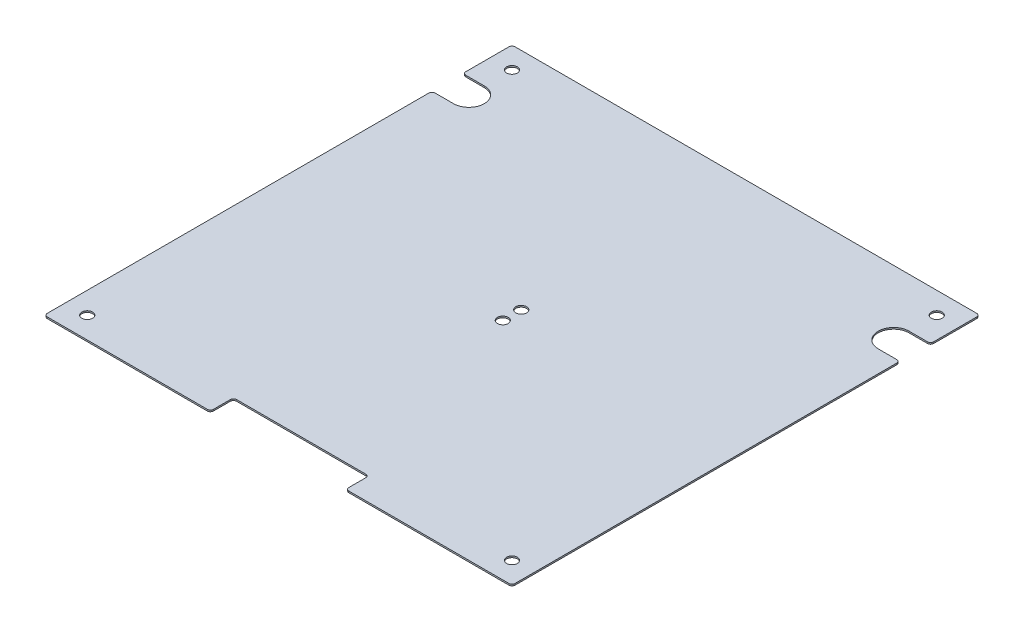
SolidWorks part; units mm, degrees
ref_plane "Front Plane" through (0, 0, 0) normal (0, 0, 1) x (1, 0, 0)
ref_plane "Top Plane" through (0, 0, 0) normal (0, 1, 0) x (1, 0, 0)
ref_plane "Right Plane" through (0, 0, 0) normal (1, 0, 0) x (0, 0, -1)
sketch "Sketch1" plane through (0, 0, 0) normal (0, 1, 0) x (1, 0, 0)
  line L1 (152, -152) -> (-152, -152)
  line L2 (152, -152) -> (152, 152)
  line L3 (152, 152) -> (-152, 152)
  line L4 (-152, -152) -> (-152, 152)
  line L5 (152, -152) -> (-152, 152) construction
  line L6 (152, 152) -> (-152, -152) construction
  point P0 (0, 0)
  dimension "D1" = 304
extrude "Boss-Extrude1" add sketch "Sketch1" along normal blind 1
sketch "Sketch2" plane through (0, 1, 0) normal (0, 1, 0) x (1, 0, 0)
  line L0 (-44, -152) -> (-44, -137)
  line L1 (-152, -152) -> (152, -152) construction
  line L2 (-44, -137) -> (44, -137)
  line L3 (44, -137) -> (44, -152)
  line L4 (44, -152) -> (-44, -152)
  line L5 (-152, 100) -> (-138, 100)
  line L6 (-152, 152) -> (-152, -152) construction
  line L8 (-138, 120) -> (-152, 120)
  line L9 (-152, 120) -> (-152, 100)
  line L10 (-152, 110) -> (-138, 110) construction
  line L11 (0, -152) -> (0, 152) construction
  line L12 (152, 152) -> (-152, 152) construction
  line L13 (152, 100) -> (138, 100)
  line L14 (152, 120) -> (152, 100)
  line L15 (138, 120) -> (152, 120)
  arc A0 (-138, 100) -> (-138, 120) centre (-138, 110) ccw
  arc A1 (138, 100) -> (138, 120) centre (138, 110) cw
  point P14 (0, 0)
  point P20 (0, 0)
  dimension "D1" = 108
  dimension "D2" = 196
  dimension "D3" = 15
  dimension "D4" = 20
  dimension "D5" = 262
  dimension "D6" = 14
extrude "Cut-Extrude1" cut sketch "Sketch2" against normal through all
fillet "Fillet1" radius 2 12 edges at (-44, 0.5, 152) (-152, 0.5, 152) (-152, 0.5, -100) (-152, 0.5, -120) (152, 0.5, -152) (152, 0.5, -120) (152, 0.5, -100) (152, 0.5, 152) (44, 0.5, 152) (44, 0.5, 137) (-44, 0.5, 137) (-152, 0.5, -152)
hole_wizard "Ø7.0 (7) Diameter Hole1" positions "Sketch3" profile "Sketch4" hole size "Ø7.0" standard "ANSI Metric" end condition up to next
sketch "Sketch3" plane through (0, 1, 0) normal (0, 1, 0) x (1, 0, 0)
  line L1 (-138, -138) -> (138, -138)
  line L2 (-138, -138) -> (-138, 138)
  line L3 (-138, 138) -> (138, 138)
  line L4 (138, -138) -> (138, 138)
  line L5 (-152, 98) -> (-152, -150) construction
  line L6 (-150, -152) -> (-46, -152) construction
  line L7 (0, 6) -> (0, -6) construction
  point P1 (-138, -138)
  point P2 (138, 138)
  point P131 (-138, 138)
  point P132 (138, -138)
  point P138 (0, -6)
  point P140 (0, 6)
  dimension "D1" = 14
  dimension "D2" = 14
  dimension "D3" = 290
  dimension "D4" = 290
  dimension "D5" = 152
  dimension "D6" = 146
  dimension "D7" = 158
sketch "Sketch4" plane through (-138, 1, 138) normal (1, 0, 0) x (0, 0, 1)
  line L0 (0, 0) -> (0, 1)
  line L1 (0, 1) -> (3.5, 1)
  line L2 (3.5, 1) -> (3.5, 0)
  line L5 (3.5, 0) -> (0, 0)
  line L11 (0, -6.35) -> (0, 107.95) construction
  dimension "Thru Hole Dia." = 7
  dimension "Thru Hole Depth" = 1
sketch "Sketch6" plane through (0, 0, 0) normal (0, -1, 0) x (1, 0, 0)
  line L0 (46, 152) -> (150, 152) construction
  line L1 (20, 97) -> (-20, 97)
  line L2 (20, 97) -> (20, 122)
  line L3 (20, 122) -> (-20, 122)
  line L4 (-20, 97) -> (-20, 122)
  line L5 (20, 97) -> (-20, 122) construction
  line L6 (20, 122) -> (-20, 97) construction
  point P0 (0, 109.5)
  point P5 (0, 0)
  point P9 (20.6341, 122)
  point P10 (21.0387, 97.9109)
  dimension "D1" = 30
  dimension "D2" = 40
  dimension "D3" = 25
extrude "Boss-Extrude2" add sketch "Sketch6" along normal blind 1
